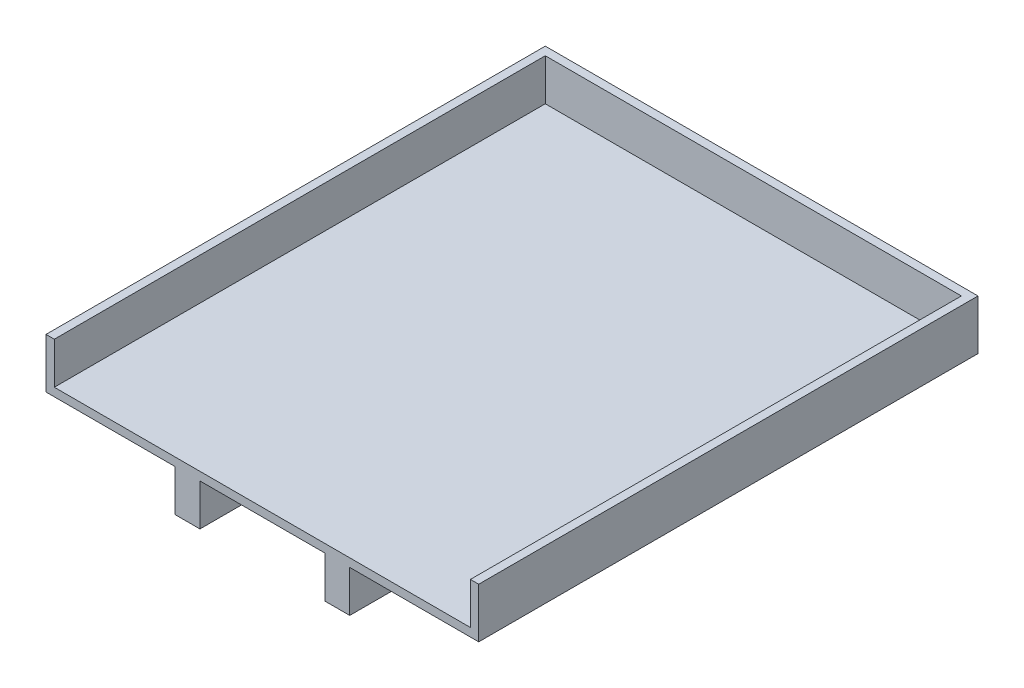
SolidWorks part; units mm, degrees
ref_plane "前视" through (0, 0, 0) normal (0, 0, 1) x (1, 0, 0)
ref_plane "上视" through (0, 0, 0) normal (0, 1, 0) x (1, 0, 0)
ref_plane "右视" through (0, 0, 0) normal (1, 0, 0) x (0, 0, -1)
sketch "Sketch1" plane through (0, 0, 0) normal (0, 0, 1) x (1, 0, 0)
  line L0 (-25, 0) -> (25, 0)
  line L1 (25, 0) -> (25, 5)
  line L2 (0, 0) -> (0, -1) construction
  line L3 (-25, 5) -> (-25, 0)
  line L4 (-26, 5) -> (-25, 5)
  line L5 (-26, 5) -> (-26, -1)
  line L6 (-7.5, -1) -> (7.5, -1)
  line L7 (26, -1) -> (26, 5)
  line L8 (25, 5) -> (26, 5)
  line L9 (10.5, -1) -> (26, -1)
  line L10 (-10.5, -1) -> (-26, -1)
  line L11 (7.5, -1) -> (7.5, -6)
  line L12 (7.5, -6) -> (10.5, -6)
  line L13 (10.5, -1) -> (10.5, -6)
  line L14 (-10.5, -1) -> (-10.5, -6)
  line L15 (-7.5, -6) -> (-10.5, -6)
  line L16 (-7.5, -1) -> (-7.5, -6)
  dimension "D1" = 50
  dimension "D3" = 1
  dimension "D2" = 5
  dimension "D5" = 52
  dimension "D6" = 6
  dimension "D7" = 1
  dimension "D8" = 5
  dimension "D9" = 3
  dimension "D10" = 15
extrude "Boss-Extrude1" add sketch "Sketch1" along normal blind 60
sketch "Sketch2" plane through (0, 0, 0) normal (0, 0, -1) x (-1, 0, 0)
  line L1 (-25, 5) -> (25, 5)
  line L2 (-25, 5) -> (-25, 0)
  line L3 (-25, 0) -> (25, 0)
  line L4 (25, 5) -> (25, 0)
extrude "Boss-Extrude2" add sketch "Sketch2" against normal blind 1
